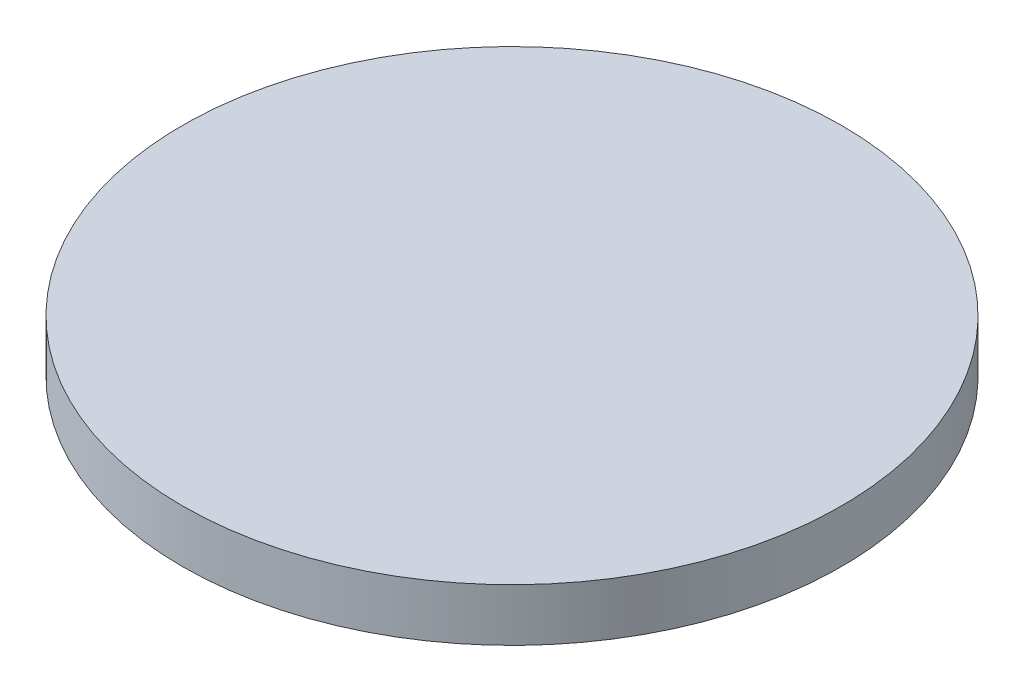
SolidWorks part; units mm, degrees
material "Copper"
ref_plane "Front Plane" through (0, 0, 0) normal (0, 0, 1) x (1, 0, 0)
ref_plane "Top Plane" through (0, 0, 0) normal (0, 1, 0) x (1, 0, 0)
ref_plane "Right Plane" through (0, 0, 0) normal (1, 0, 0) x (0, 0, -1)
sketch "Sketch1" plane through (0, 0, 0) normal (0, 1, 0) x (1, 0, 0)
  circle A0 centre (0, 0) radius 9.525
  dimension "D1" = 19.05
extrude "Boss-Extrude1" add sketch "Sketch1" along normal blind 1.52
